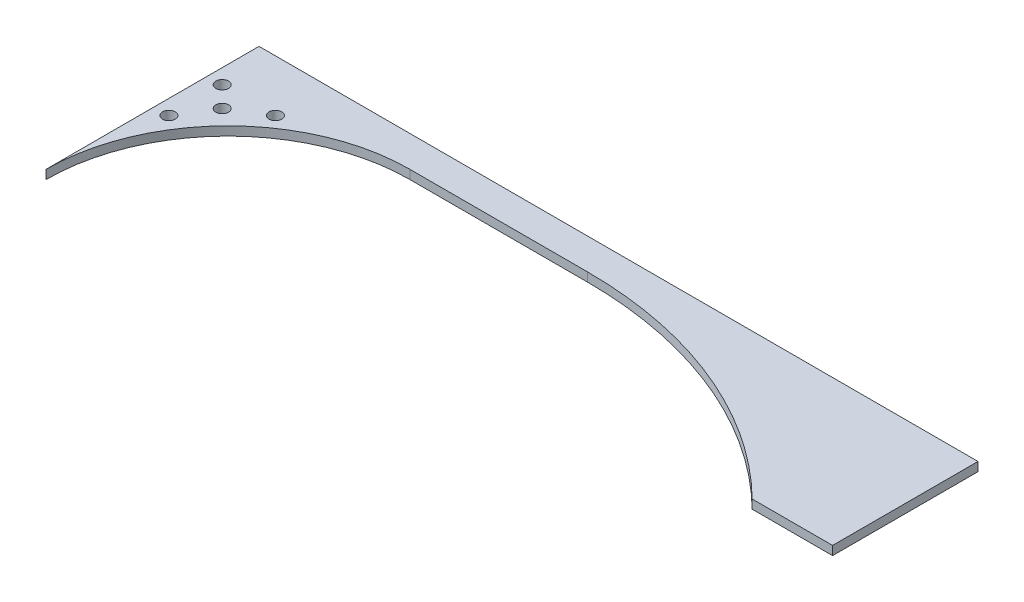
SolidWorks part; units mm, degrees
material "Acrylic (Medium-high impact)"
ref_plane "Front Plane" through (0, 0, 0) normal (0, 0, 1) x (1, 0, 0)
ref_plane "Top Plane" through (0, 0, 0) normal (0, 1, 0) x (1, 0, 0)
ref_plane "Right Plane" through (0, 0, 0) normal (1, 0, 0) x (0, 0, -1)
sketch "Sketch1" plane through (0, 0, 0) normal (0, 1, 0) x (1, 0, 0)
  line L6 (-257.175, 0) -> (-257.175, -152.4) construction
  line L11 (-257.175, 0) -> (257.175, 0)
  line L13 (257.175, 0) -> (257.175, -104.0325)
  line L14 (0, -22.225) -> (0, 0) construction
  line L15 (0, -22.225) -> (257.175, -22.225) construction
  line L16 (0, -22.225) -> (-127, -22.225)
  line L17 (257.175, -104.0325) -> (199.6702, -104.0325)
  line L19 (-276.225, -50.8) -> (-276.225, -152.4)
  line L20 (-276.225, -152.4) -> (-257.175, -152.4)
  line L21 (-276.225, -50.8) -> (-257.175, -50.8)
  line L22 (-257.175, -50.8) -> (-257.175, 0)
  arc A5 (0, -22.225) -> (199.6702, -104.0325) centre (0, -306.7995) cw
  arc A6 (-127, -22.225) -> (-257.175, -152.4) centre (-127, -152.4) ccw
  point P2 (0, 0)
  dimension "D5" = 127
  dimension "D1" = 514.35
  dimension "D2" = 22.225
  dimension "D3" = 19.05
  dimension "D4" = 50.8
extrude "Boss-Extrude1" add sketch "Sketch1" along normal blind 6.35
sketch "Sketch2" plane through (0, 0, 0) normal (0, 1, 0) x (1, 0, 0)
  line L0 (-276.225, -152.4) -> (-257.175, -152.4) construction
  line L1 (-276.225, -50.8) -> (-257.175, -50.8)
  line L2 (-276.225, -50.8) -> (-276.225, -152.4)
  line L3 (-276.225, -152.4) -> (-257.175, -152.4)
  line L4 (-257.175, -50.8) -> (-257.175, -152.4)
extrude "Cut-Extrude2" cut sketch "Sketch2" along normal through all
sketch "Sketch3" plane through (0, 6.35, 0) normal (0, 1, 0) x (1, 0, 0)
  circle A0 centre (-208.4525, -36.9612) radius 4.572 construction
  circle A1 centre (-246.5525, -36.9612) radius 4.572 construction
  circle A2 centre (-231.8555, -51.6583) radius 4.572 construction
  circle A3 centre (-246.5525, -75.0612) radius 4.572 construction
  circle A4 centre (-208.4525, -36.9612) radius 4.572
  circle A5 centre (-246.5525, -36.9612) radius 4.572
  circle A6 centre (-231.8555, -51.6583) radius 4.572
  circle A7 centre (-246.5525, -75.0612) radius 4.572
extrude "Cut-Extrude3" cut sketch "Sketch3" against normal through all
